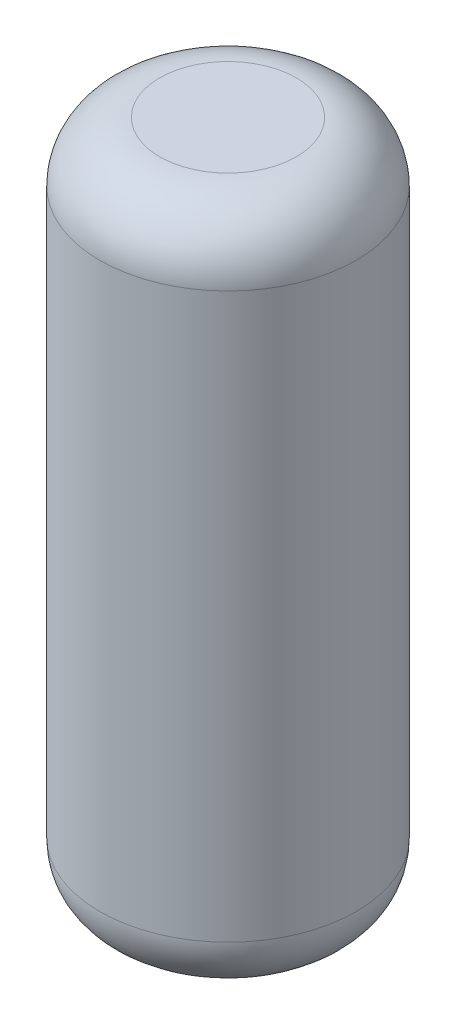
SolidWorks part; units mm, degrees
ref_plane "Front Plane" through (0, 0, 0) normal (0, 0, 1) x (1, 0, 0)
ref_plane "Top Plane" through (0, 0, 0) normal (0, 1, 0) x (1, 0, 0)
ref_plane "Right Plane" through (0, 0, 0) normal (1, 0, 0) x (0, 0, -1)
sketch "Sketch1" plane through (0, 0, 0) normal (0, 0, 1) x (1, 0, 0)
  line L0 (0, 0) -> (0, 3616.1289) construction
  line L1 (0, 3616.1289) -> (-400, 3616.1289)
  line L2 (-750, 3266.1289) -> (-750, -33.8711)
  line L3 (-400, -383.8711) -> (0, -383.8711)
  line L4 (0, -383.8711) -> (0, -283.8711)
  line L5 (0, -283.8711) -> (-50, -283.8711)
  line L6 (-400, 66.1289) -> (-400, 3166.1289)
  line L7 (-50, 3516.1289) -> (0, 3516.1289)
  line L8 (0, 3516.1289) -> (0, 3616.1289)
  arc A0 (-750, -33.8711) -> (-400, -383.8711) centre (-400, -33.8711) ccw
  arc A1 (-50, -283.8711) -> (-400, 66.1289) centre (-50, 66.1289) cw
  arc A2 (-400, 3166.1289) -> (-50, 3516.1289) centre (-50, 3166.1289) cw
  arc A3 (-400, 3616.1289) -> (-750, 3266.1289) centre (-400, 3266.1289) ccw
  dimension "filletradius" = 350
  dimension "height" = 4000
  dimension "top_lid" = 100
  dimension "bottom_lid" = 100
  dimension "outerradius" = 750
  dimension "inner_radius" = 400
revolve "Revolve1" add sketch "Sketch1" angle 360 about L0
